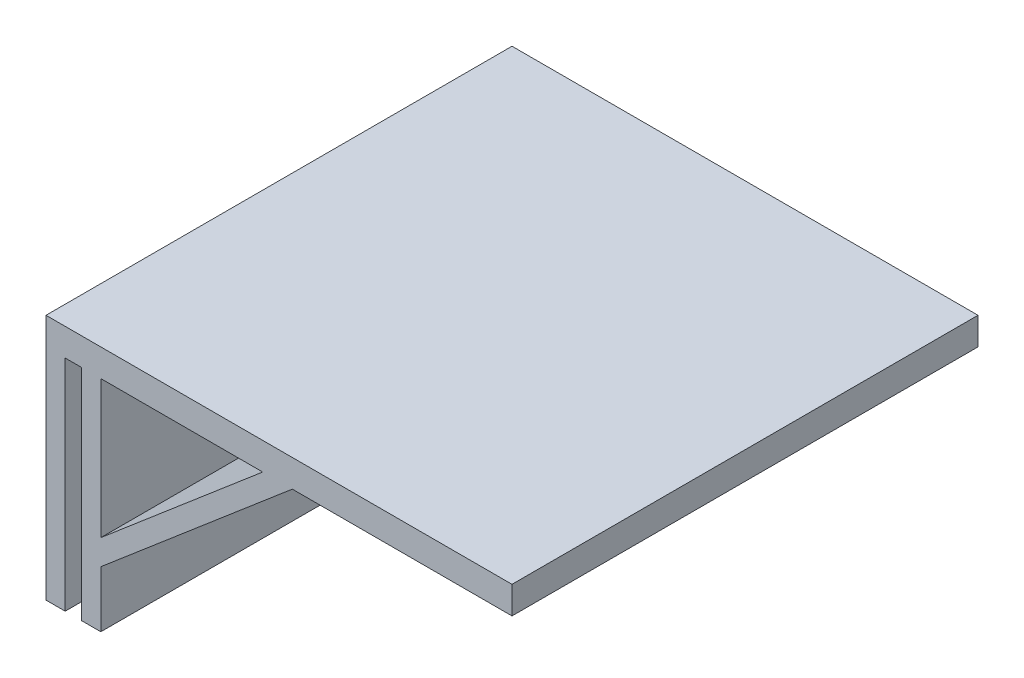
SolidWorks part; units mm, degrees
ref_plane "Plan de face" through (0, 0, 0) normal (0, 0, 1) x (1, 0, 0)
ref_plane "Plan de dessus" through (0, 0, 0) normal (0, 1, 0) x (1, 0, 0)
ref_plane "Plan de droite" through (0, 0, 0) normal (1, 0, 0) x (0, 0, -1)
sketch "Esquisse1" plane through (0, 0, 0) normal (0, 0, 1) x (1, 0, 0)
  line L0 (0, 0) -> (0, 90)
  line L1 (0, 90) -> (170, 90)
  line L2 (170, 90) -> (170, 80)
  line L3 (170, 80) -> (95, 80)
  line L4 (20, 80) -> (20, 29.7533)
  line L5 (20, 0) -> (13, 0)
  line L6 (13, 0) -> (13, 80)
  line L7 (13, 80) -> (7, 80)
  line L8 (7, 80) -> (7, 0)
  line L9 (7, 0) -> (0, 0)
  line L10 (20, 29.7533) -> (79.059, 80)
  line L11 (89.8615, 80) -> (95, 80)
  line L13 (89.8615, 80) -> (99.6489, 80)
  line L15 (20, 10.1928) -> (20, 20.5626)
  line L16 (79.059, 80) -> (20, 80)
  line L17 (20, 10.1928) -> (20, 0)
  line L18 (20, 20.5626) -> (89.8615, 80)
  line L19 (24.536, 24.4218) -> (83.595, 74.6685) construction
  dimension "D1" = 7
  dimension "D2" = 7
  dimension "D3" = 6
  dimension "D4" = 90
  dimension "D5" = 80
  dimension "D6" = 80
  dimension "D7" = 170
  dimension "D8" = 7
extrude "Boss.-Extru.1" add sketch "Esquisse1" along normal blind 170
sketch "Esquisse3" plane through (0, 0, 170) normal (0, 0, 1) x (1, 0, 0)
  line L0 (20, 80) -> (79.059, 80)
  line L1 (79.059, 80) -> (20, 29.7533)
  line L2 (20, 80) -> (20, 29.7533)
  line L4 (13, 0) -> (13, 80) construction
  line L5 (0, 90) -> (170, 90) construction
  line L6 (20, 20.5626) -> (89.8615, 80) construction
  dimension "D1" = 7
  dimension "D2" = 10
  dimension "D3" = 7
extrude "Enlèv. mat.-Extru.1" cut sketch "Esquisse3" against normal through all
